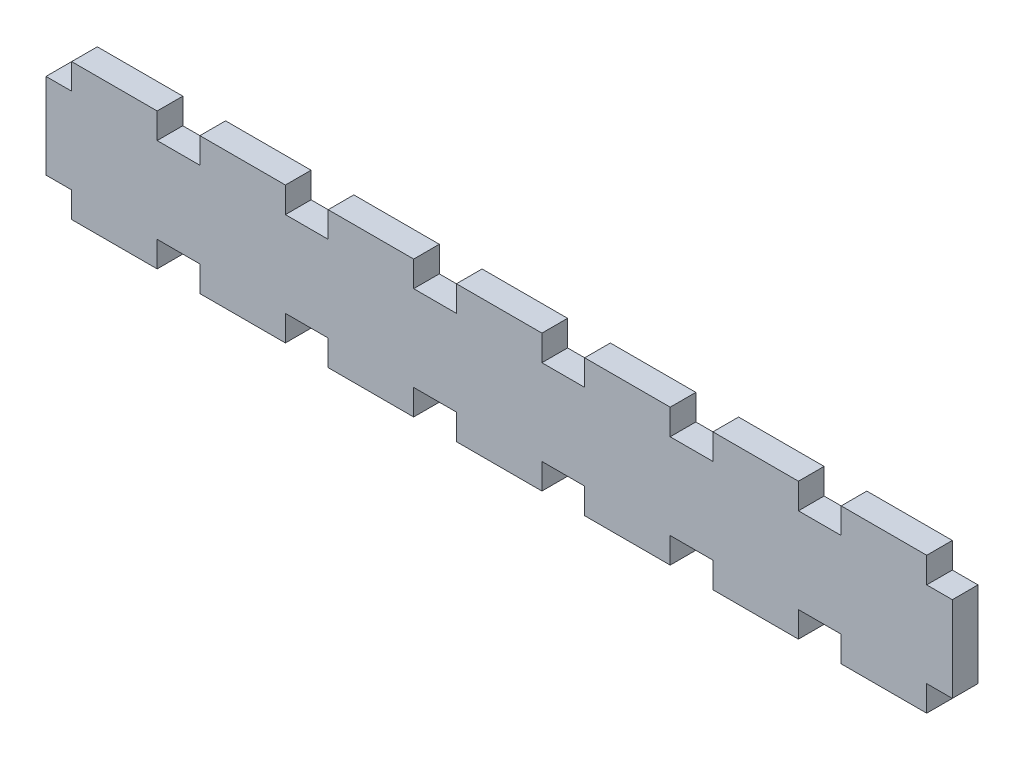
SolidWorks part; units mm, degrees
material "Thornel Mat VMA"
ref_plane "前视基准面" through (0, 0, 0) normal (0, 0, 1) x (1, 0, 0)
ref_plane "上视基准面" through (0, 0, 0) normal (0, 1, 0) x (1, 0, 0)
ref_plane "右视基准面" through (0, 0, 0) normal (1, 0, 0) x (0, 0, -1)
sketch "草图1" plane through (0, 0, 0) normal (0, 0, 1) x (1, 0, 0)
  line L0 (-35, 5) -> (-35, 8)
  line L1 (-53, 5) -> (-50, 5)
  line L2 (-53, 5) -> (-53, -5)
  line L3 (-53, -5) -> (-50, -5)
  line L4 (53, 5) -> (53, -5)
  line L5 (-53, 5) -> (53, -5) construction
  line L6 (-53, -5) -> (53, 5) construction
  line L8 (-50, 5) -> (-50, 8)
  line L9 (-50, 8) -> (-40, 8)
  line L10 (-40, 5) -> (-40, 8)
  line L12 (-25, 5) -> (-25, 8)
  line L13 (-35, 8) -> (-25, 8)
  line L14 (-20, 5) -> (-20, 8)
  line L16 (-10, 5) -> (-10, 8)
  line L17 (-20, 8) -> (-10, 8)
  line L18 (-5, 5) -> (-5, 8)
  line L20 (5, 5) -> (5, 8)
  line L21 (-5, 8) -> (5, 8)
  line L22 (10, 5) -> (10, 8)
  line L24 (20, 5) -> (20, 8)
  line L25 (10, 8) -> (20, 8)
  line L26 (25, 5) -> (25, 8)
  line L28 (35, 5) -> (35, 8)
  line L29 (25, 8) -> (35, 8)
  line L30 (40, 5) -> (40, 8)
  line L32 (50, 5) -> (50, 8)
  line L33 (40, 8) -> (50, 8)
  line L34 (55, 0) -> (-55, 0) construction
  line L36 (50, -5) -> (50, -8)
  line L37 (40, -8) -> (50, -8)
  line L38 (40, -5) -> (40, -8)
  line L40 (35, -5) -> (35, -8)
  line L41 (25, -8) -> (35, -8)
  line L42 (25, -5) -> (25, -8)
  line L44 (20, -5) -> (20, -8)
  line L45 (10, -8) -> (20, -8)
  line L46 (10, -5) -> (10, -8)
  line L48 (5, -5) -> (5, -8)
  line L49 (-5, -8) -> (5, -8)
  line L50 (-5, -5) -> (-5, -8)
  line L52 (-10, -5) -> (-10, -8)
  line L53 (-20, -8) -> (-10, -8)
  line L54 (-20, -5) -> (-20, -8)
  line L56 (-25, -5) -> (-25, -8)
  line L57 (-35, -8) -> (-25, -8)
  line L58 (-35, -5) -> (-35, -8)
  line L59 (-50, -8) -> (-40, -8)
  line L60 (-40, -5) -> (-40, -8)
  line L62 (-50, -5) -> (-50, -8)
  line L63 (-40, 5) -> (-35, 5)
  line L64 (-25, 5) -> (-20, 5)
  line L65 (-10, 5) -> (-5, 5)
  line L66 (5, 5) -> (10, 5)
  line L67 (20, 5) -> (25, 5)
  line L68 (35, 5) -> (40, 5)
  line L69 (50, 5) -> (53, 5)
  line L70 (-40, -5) -> (-35, -5)
  line L71 (-25, -5) -> (-20, -5)
  line L72 (-10, -5) -> (-5, -5)
  line L73 (5, -5) -> (10, -5)
  line L74 (20, -5) -> (25, -5)
  line L75 (35, -5) -> (40, -5)
  line L76 (50, -5) -> (53, -5)
  point P0 (0, 0)
  dimension "D1" = 106
  dimension "D2" = 10
  dimension "D3" = 10
  dimension "D4" = 3
  dimension "D5" = 3
  dimension "D6" = 7
extrude "凸台-拉伸1" add sketch "草图1" along normal blind 3
